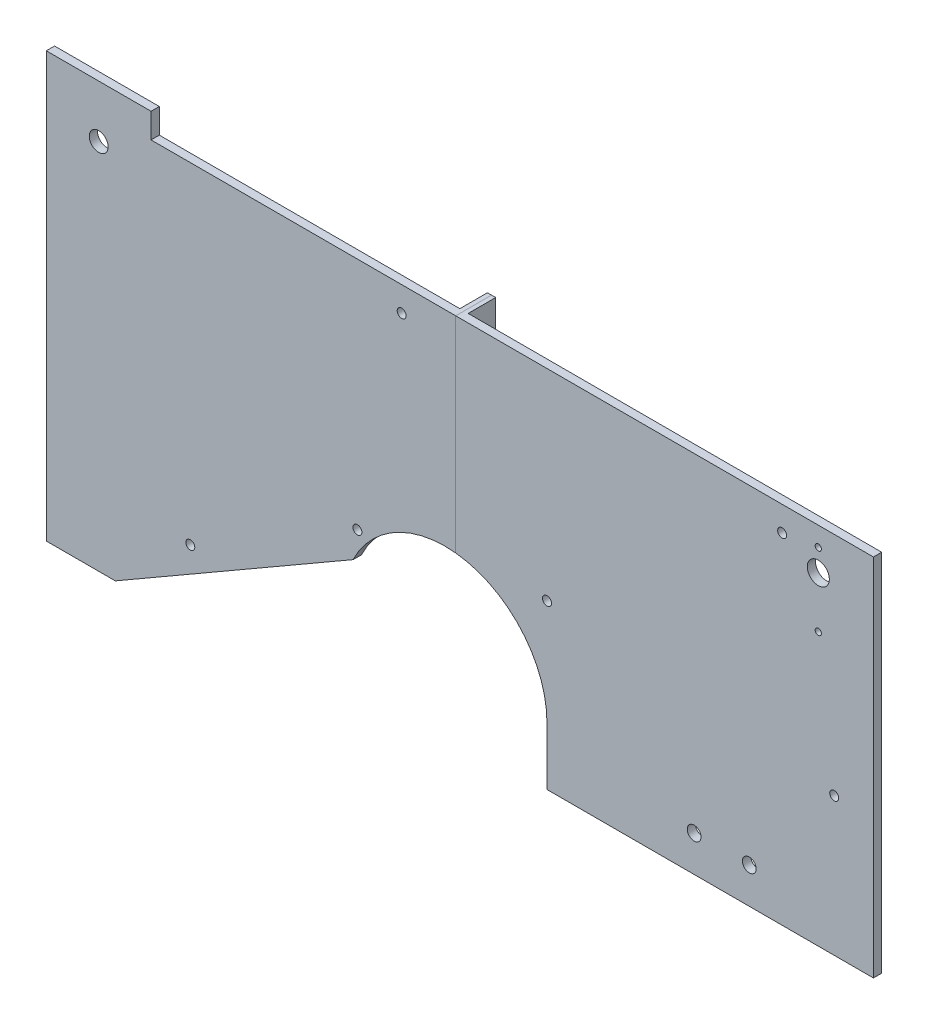
SolidWorks part; units mm, degrees
ref_plane "Front Plane" through (0, 0, 0) normal (0, 0, 1) x (1, 0, 0)
ref_plane "Top Plane" through (0, 0, 0) normal (0, 1, 0) x (1, 0, 0)
ref_plane "Right Plane" through (0, 0, 0) normal (1, 0, 0) x (0, 0, -1)
sketch "Sketch2" plane through (0, 0, 0) normal (0, 0, 1) x (1, 0, 0)
  line L0 (25.0304, 0) -> (111.2865, 49.8)
  line L1 (0, 0) -> (25.0304, 0)
  line L2 (0, 0) -> (0, 154)
  line L4 (300, 0) -> (300, 145)
  line L5 (181.6, 33.7) -> (181.6, 0)
  line L6 (181.6, 0) -> (300, 0)
  line L7 (19, 135) -> (19, 164.3674) construction
  line L11 (38, 145) -> (300, 145)
  line L12 (0, 154) -> (19, 154)
  line L13 (19, 154) -> (38, 154)
  line L14 (38, 154) -> (38, 145)
  line L15 (19, 135) -> (50019, 135) construction
  line L20 (19, 135) -> (19, -49865) construction
  circle A0 centre (19, 135) radius 3.425
  arc A1 (181.6, 33.7) -> (111.2865, 49.8) centre (144.6, 33.7) ccw
  point P19 (19, 154)
  dimension "D3" = 135
  dimension "D4" = 19
  dimension "D5" = 6.85
  dimension "D6" = 74
  dimension "D7" = 155.4
  dimension "D8" = 33.7
  dimension "D1" = 300
  dimension "D2" = 154
  dimension "D9" = 30
  dimension "D10" = 99.6
  dimension "D11" = 19
extrude "Boss-Extrude2" add sketch "Sketch2" along normal blind 3
sketch "Sketch3" plane through (0, 0, 3) normal (0, 0, 1) x (1, 0, 0)
  line L0 (300, 0) -> (300, 145) construction
  line L1 (181.6, 0) -> (300, 0)
  line L2 (181.6, 0) -> (181.6, 12.75)
  line L3 (181.6, 12.75) -> (300, 12.75)
  line L4 (300, 0) -> (300, 12.75)
  dimension "D1" = 12.75
extrude "Cut-Extrude1" cut sketch "Sketch3" against normal through all
sketch "Sketch4" plane through (0, 0, 3) normal (0, 0, 1) x (1, 0, 0)
  line L0 (19, 135) -> (19, -49865) construction
  line L1 (19, 135) -> (-49981, 135) construction
sketch "Sketch5" plane through (0, 0, 3) normal (0, 0, 1) x (1, 0, 0)
  line L0 (300, 12.75) -> (300, 145) construction
  line L1 (300, 12.75) -> (181.6, 12.75) construction
  line L2 (300, 145) -> (38, 145) construction
  line L3 (0, 154) -> (0, 0) construction
  line L4 (0, 0) -> (25.0304, 0) construction
  circle A0 centre (254.98, 25.75) radius 2.5
  circle A1 centre (234.98, 25.75) radius 2.5
  circle A2 centre (280, 130) radius 4
  circle A3 centre (280, 138) radius 1.125
  circle A4 centre (280, 111.5) radius 1.125
  circle A5 centre (181.6, 72.03) radius 1.625
  circle A6 centre (285.78, 62.92) radius 1.625
  circle A7 centre (52.23, 24.91) radius 1.625
  circle A8 centre (112.84, 59.93) radius 1.625
  circle A9 centre (266.89, 135.99) radius 1.625
  circle A10 centre (128.89, 135.99) radius 1.625
  dimension "D1" = 5
  dimension "D2" = 45.02
  dimension "D3" = 13
  dimension "D4" = 5
  dimension "D5" = 20
  dimension "D6" = 13
  dimension "D9" = 8
  dimension "D10" = 2.25
  dimension "D11" = 8
  dimension "D12" = 20
  dimension "D13" = 18.5
  dimension "D14" = 20
  dimension "D15" = 2.25
  dimension "D16" = 3.25
  dimension "D17" = 118.4
  dimension "D18" = 72.97
  dimension "D19" = 3.25
  dimension "D20" = 14.22
  dimension "D21" = 82.08
  dimension "D22" = 52.23
  dimension "D23" = 3.25
  dimension "D24" = 24.91
  dimension "D25" = 112.84
  dimension "D26" = 3.25
  dimension "D27" = 59.93
  dimension "D28" = 9.01
  dimension "D29" = 3.25
  dimension "D30" = 33.11
  dimension "D31" = 3.25
  dimension "D32" = 9.01
  dimension "D33" = 138
  dimension "D7" = 20
  dimension "D8" = 15
extrude "Cut-Extrude2" cut sketch "Sketch5" against normal through all
sketch "Sketch12" plane through (0, 0, 0) normal (0, 0, -1) x (-1, 0, 0)
  line L0 (-300, 145) -> (-38, 145) construction
  line L1 (-150, 145) -> (-147, 145)
  line L2 (-150, 145) -> (-150, 75)
  line L3 (-150, 75) -> (-147, 75)
  line L4 (-147, 145) -> (-147, 75)
  line L5 (-300, 12.75) -> (-300, 145) construction
  dimension "D1" = 3
  dimension "D2" = 70
  dimension "D3" = 153
extrude "Boss-Extrude6" add sketch "Sketch12" along normal blind 10
sketch "Sketch15" plane through (150, 0, 0) normal (1, 0, 0) x (0, 0, -1)
  line L0 (10, 145) -> (0, 145) construction
  line L1 (10, 145) -> (10, 75) construction
  line L2 (10, 75) -> (0, 75) construction
  circle A0 centre (5, 135) radius 1.625
  circle A1 centre (5, 110) radius 1.625
  circle A2 centre (5, 85) radius 1.625
  dimension "D1" = 3.25
  dimension "D2" = 10
  dimension "D3" = 5
  dimension "D4" = 3.25
  dimension "D5" = 5
  dimension "D6" = 25
  dimension "D7" = 3.25
  dimension "D8" = 5
  dimension "D9" = 10
extrude "Cut-Extrude5" cut sketch "Sketch15" against normal up to next
sketch "Sketch16" plane through (0, 0, -10) normal (0, 0, -1) x (-1, 0, 0)
  line L0 (-148.5, 145) -> (-148.5, 70.4939)
  line L1 (-147, 145) -> (-150, 145) construction
  arc A0 (-111.2865, 49.8) -> (-181.6, 33.7) centre (-144.6, 33.7) ccw construction
split "Split4" trim tools "Sketch16" bodies to split 118 resulting bodies 119 120
